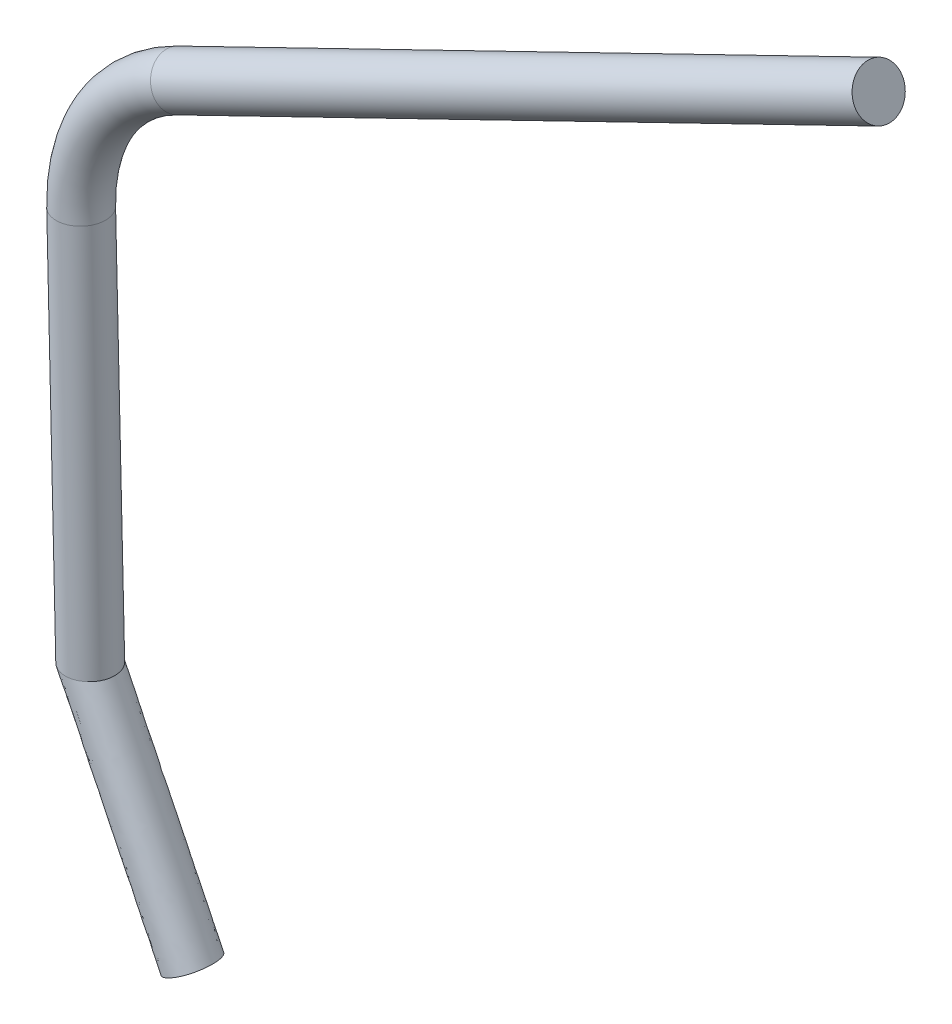
SolidWorks part; units mm, degrees
material "Cast Carbon Steel"
ref_plane "Front Plane" through (0, 0, 0) normal (0, 0, 1) x (1, 0, 0)
ref_plane "Top Plane" through (0, 0, 0) normal (0, 1, 0) x (1, 0, 0)
ref_plane "Right Plane" through (0, 0, 0) normal (1, 0, 0) x (0, 0, -1)
sketch "Sketch4" plane through (0, 0, 0) normal (0, 0, 1) x (1, 0, 0)
  arc A0 (-38.8747, 79.9498) -> (-88.8758, -2.0729) centre (0, 0) ccw
  dimension "D1" = 88.9
sketch "Sketch5" plane through (0, 0, 0) normal (0, 1, 0) x (1, 0, 0)
  circle A0 centre (-88.8758, 0) radius 12.7
  dimension "D1" = 25.4
sweep "Sweep1" add profiles "Sketch5" path "Sketch4"
ref_plane "Plane4" through (0, 0, 0) normal (0.8993, 0.4373, 0) x (0, 0, -1)
sketch "Sketch6" plane through (0, 0, 0) normal (0.8993, 0.4373, 0) x (0, 0, -1)
  circle A0 centre (0, 88.8758) radius 12.7
extrude "Boss-Extrude3" add sketch "Sketch6" along normal blind 406.4
ref_plane "Plane5" through (0, 0, 0) normal (0.0233, -0.9997, 0) x (-0.9997, -0.0233, 0)
sketch "Sketch7" plane through (0, 0, 0) normal (0.0233, -0.9997, 0) x (-0.9997, -0.0233, 0)
  circle A0 centre (88.8758, 0) radius 12.7
extrude "Boss-Extrude4" add sketch "Sketch7" along normal blind 203.2
ref_plane "Plane7" through (0, 0, -12.7) normal (0, 0, -1) x (-1, 0, 0)
sketch "Sketch9" plane through (0, 0, -12.7) normal (0, 0, -1) x (-1, 0, 0)
  line L0 (33.3106, 68.5067) -> (44.4176, 91.3495) construction
  line L1 (76.1551, -1.7762) -> (101.5482, -2.3685) construction
  circle A0 centre (76.2699, 46.4942) radius 12.065
  dimension "D1" = 24.13
  dimension "D2" = 48.26
  dimension "D3" = 48.26
extrude "Cut-Extrude2" cut sketch "Sketch9" against normal blind 6.35
ref_plane "Plane8" through (4.7381, -203.1448, 0) normal (0.0233, -0.9997, 0) x (-0.9997, -0.0233, 0)
sketch "Sketch10" plane through (4.7381, -203.1448, 0) normal (0.0233, -0.9997, 0) x (-0.9997, -0.0233, 0)
  circle A0 centre (88.8758, 0) radius 12.7
sketch "Sketch11" plane through (0, 0, 0) normal (0, 0, 1) x (1, 0, 0)
  line L0 (-84.1136, -205.2171) -> (-28.5784, -319.4311)
  line L1 (24.0507, -49.4628) -> (-24.0507, 49.4628) construction
  dimension "D1" = 127
sweep "Sweep2" add profiles "Sketch10" path "Sketch11"
sketch "Sketch12" plane through (0, 0, 0) normal (0, 0, 1) x (1, 0, 0)
  line L0 (-41.2749, -319.7272) -> (-20.5045, -309.6279)
  line L1 (-15.8818, -319.135) -> (-71.417, -204.921) construction
  line L2 (-20.5045, -309.6279) -> (-15.8818, -319.135)
  line L3 (-15.8818, -319.135) -> (-41.2749, -319.7272)
extrude "Cut-Extrude3" cut sketch "Sketch12" against normal through all both and the other way through all
